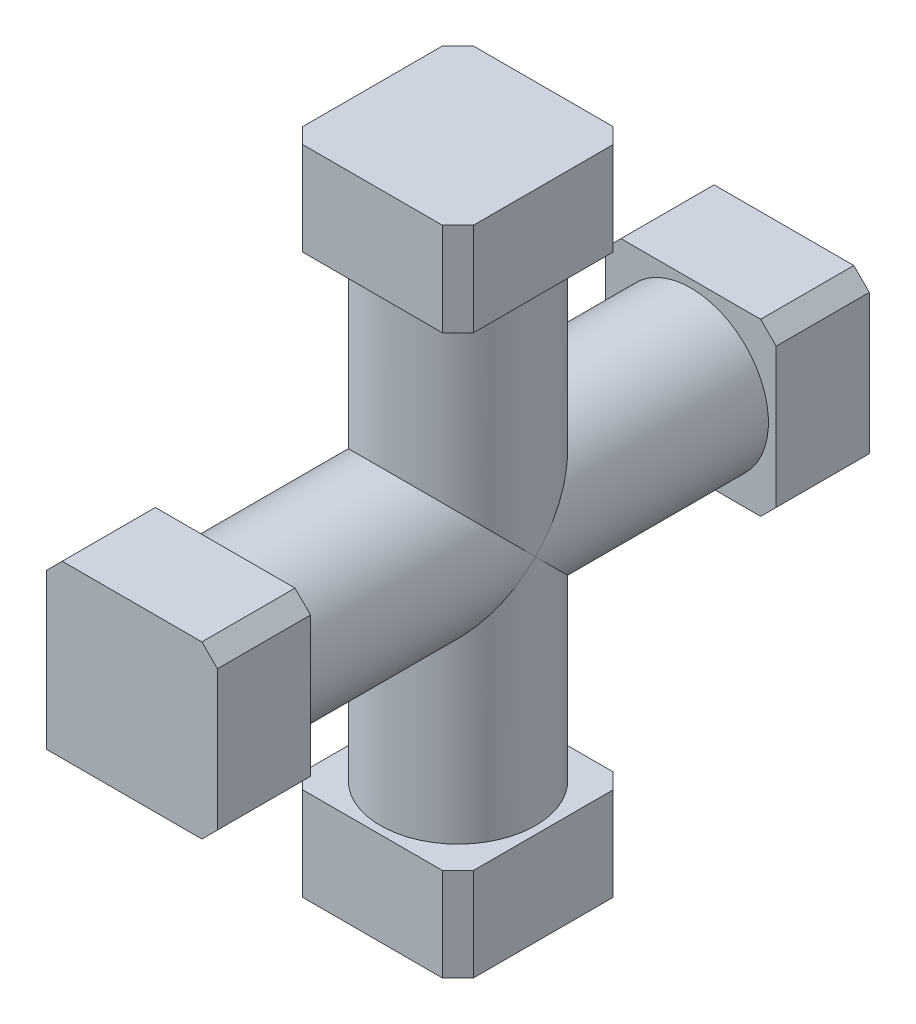
SolidWorks part; units mm, degrees
ref_plane "Front Plane" through (0, 0, 0) normal (0, 0, 1) x (1, 0, 0)
ref_plane "Top Plane" through (0, 0, 0) normal (0, 1, 0) x (1, 0, 0)
ref_plane "Right Plane" through (0, 0, 0) normal (1, 0, 0) x (0, 0, -1)
sketch "Sketch1" plane through (0, 0, 0) normal (0, 0, 1) x (1, 0, 0)
  circle A0 centre (0, 0) radius 2.5
  dimension "D1" = 5
extrude "Boss-Extrude1" add sketch "Sketch1" along normal blind 15
sketch "Sketch2" plane through (0, 0, 0) normal (0, 1, 0) x (1, 0, 0)
  line L0 (0, 0) -> (0, -15) construction
  line L1 (-2.5, -15) -> (2.5, -15) construction
sketch "Sketch3" plane through (0, 0, 0) normal (0, 1, 0) x (1, 0, 0)
  line L0 (0, 0) -> (0, -15) construction
  circle A0 centre (0, -7.5) radius 2.5
  point P2 (0, -7.5)
  dimension "D1" = 5
extrude "Boss-Extrude2" add sketch "Sketch3" along normal mid plane 15
sketch "Sketch4" plane through (0, 0, 0) normal (0, 0, -1) x (-1, 0, 0)
  line L1 (-2.75, 2.75) -> (2.75, 2.75)
  line L2 (-2.75, 2.75) -> (-2.75, -2.75)
  line L3 (-2.75, -2.75) -> (2.75, -2.75)
  line L4 (2.75, 2.75) -> (2.75, -2.75)
  dimension "D1" = 5.5
  dimension "D2" = 5.5
  dimension "D3" = 2.75
  dimension "D4" = 2.75
extrude "Boss-Extrude3" add sketch "Sketch4" along normal blind 3
chamfer "Chamfer1" distance 0.5 angle 45 1 edges at (-2.75, 2.75, -1.5)
chamfer "Chamfer2" distance 0.5 angle 45 2 edges at (2.75, 2.75, -1.5) (2.75, -2.75, -1.5)
chamfer "Chamfer3" distance 0.5 angle 45 1 edges at (-2.75, -2.75, -1.5)
ref_plane "Plane1" through (0, 0, 7.5) normal (0, 0, -1) x (-1, 0, 0)
mirror "Mirror1" about plane through (0, 0, 7.5) normal (0, 0, -1) of "Chamfer2", "Chamfer1", "Boss-Extrude3"
sketch "Sketch5" plane through (0, 7.5, 0) normal (0, 1, 0) x (1, 0, 0)
  line L1 (-2.75, -4.7529) -> (2.75, -4.7529)
  line L2 (-2.75, -4.7529) -> (-2.75, -10.2529)
  line L3 (-2.75, -10.2529) -> (2.75, -10.2529)
  line L4 (2.75, -4.7529) -> (2.75, -10.2529)
  line L6 (0, 0) -> (0, -15) construction
  line L7 (4.125, -7.5) -> (-4.125, -7.5) construction
  dimension "D1" = 5.5
  dimension "D2" = 5.5
  dimension "D3" = 2.75
  dimension "D4" = 2.7529
extrude "Boss-Extrude4" add sketch "Sketch5" along normal blind 3
chamfer "Chamfer4" distance 0.5 angle 45 3 edges at (2.75, 9, 4.7529) (-2.75, 9, 4.7529) (-2.75, 9, 10.2529)
chamfer "Chamfer5" distance 0.5 angle 45 1 edges at (2.75, 9, 10.2529)
ref_plane "Plane2" through (0, 0, 0) normal (0, -1, 0) x (-1, 0, 0)
mirror "Mirror2" about plane through (0, 0, 0) normal (0, -1, 0) of "Chamfer5", "Chamfer4", "Boss-Extrude4"
